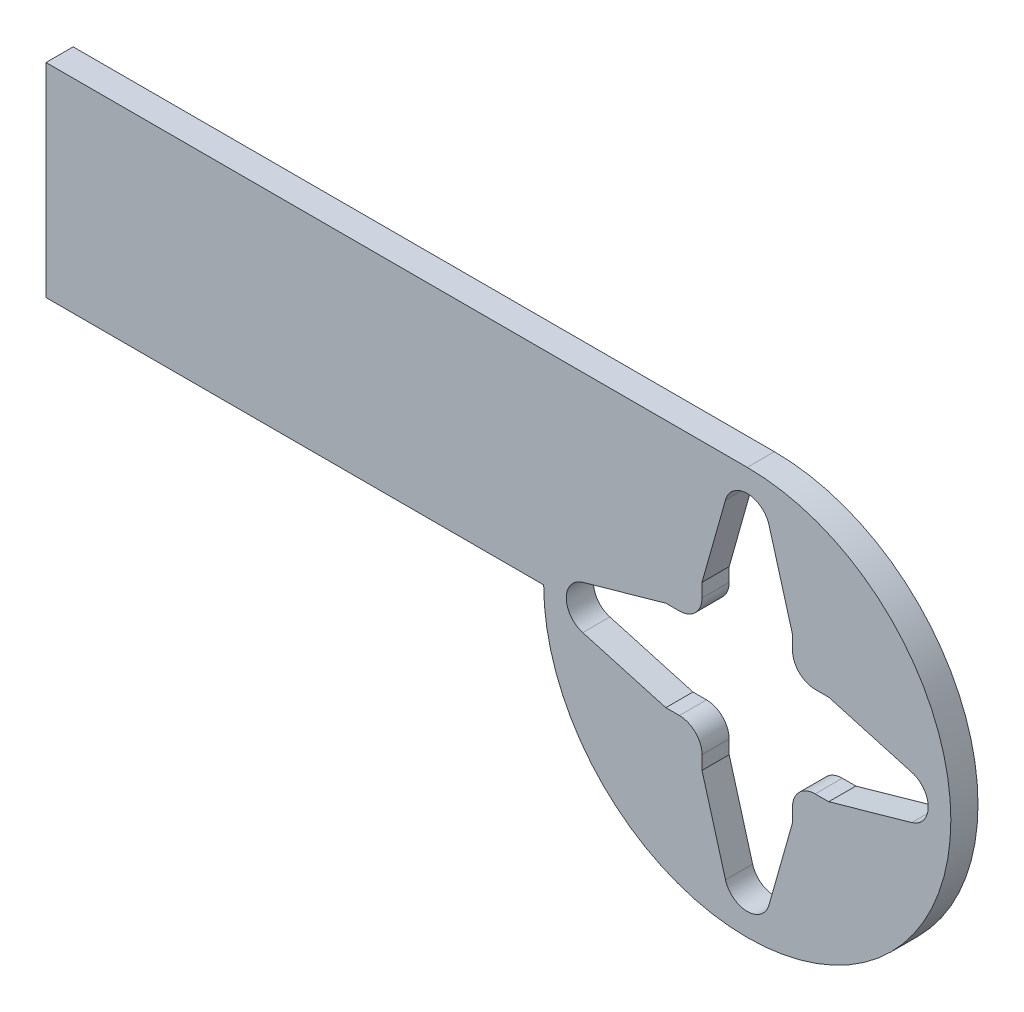
SolidWorks part; units mm, degrees
ref_plane "Front Plane" through (0, 0, 0) normal (0, 0, 1) x (1, 0, 0)
ref_plane "Top Plane" through (0, 0, 0) normal (0, 1, 0) x (1, 0, 0)
ref_plane "Right Plane" through (0, 0, 0) normal (1, 0, 0) x (0, 0, -1)
sketch "Sketch1" plane through (0, 0, 0) normal (0, 0, 1) x (1, 0, 0)
  line L0 (-5, 5) -> (-5, 9)
  line L8 (5, -5) -> (-5, -5)
  line L9 (5, -5) -> (5, 5)
  line L10 (5, 5) -> (-5, 5)
  line L11 (-5, -5) -> (-5, 5)
  line L12 (5, -5) -> (-5, 5) construction
  line L13 (5, 5) -> (-5, -5) construction
  line L14 (-5, 9) -> (-2.4058, 18.1799)
  line L15 (0, -55) -> (0, 55) construction
  line L16 (9, 5) -> (18.1799, 2.4058)
  line L17 (5, 5) -> (5, 9)
  line L18 (55, 0) -> (-55, 0) construction
  line L19 (5, -5) -> (5, -9)
  line L20 (-5, -9) -> (-2.4058, -18.1799)
  line L21 (5, -9) -> (2.4058, -18.1799)
  line L22 (-5, -5) -> (-5, -9)
  line L23 (5, -5) -> (9, -5)
  line L24 (9, -5) -> (18.1799, -2.4058)
  line L25 (-9, -5) -> (-18.1799, -2.4058)
  line L26 (5, 5) -> (9, 5)
  line L27 (-5, -5) -> (-9, -5)
  line L28 (-9, 5) -> (-18.1799, 2.4058)
  line L29 (5, 9) -> (2.4058, 18.1799)
  line L30 (-5, 5) -> (-9, 5)
  line L31 (0, 22.5) -> (-22.5, 0)
  line L32 (-22.5, 0) -> (-22.5, 22.5)
  line L33 (-22.5, 22.5) -> (0, 22.5)
  line L35 (-22.5, 22.5) -> (-77.5, 22.5)
  line L36 (-22.5, 22.5) -> (-22.5, 0)
  line L37 (-22.5, 0) -> (-77.5, 0)
  line L38 (-77.5, 22.5) -> (-77.5, 0)
  circle A0 centre (0, 0) radius 22.5
  circle A1 centre (0, 17.5) radius 2.5
  circle A2 centre (0, -17.5) radius 2.5
  circle A3 centre (17.5, 0) radius 2.5
  circle A4 centre (-17.5, 0) radius 2.5
  circle A5 centre (-7.5, 7.5) radius 2.5
  circle A6 centre (-7.5, -7.5) radius 2.5
  circle A7 centre (7.5, 7.5) radius 2.5
  circle A8 centre (7.5, -7.5) radius 2.5
  arc A9 (-24.8747, 0) -> (-22.3872, -2.25) centre (-24.8747, -2.5) cw
  point P53 (-25.9742, -5)
  point P54 (-22.2598, -3.2792)
  dimension "D1" = 45
  dimension "D3" = 5
  dimension "D5" = 12.5
  dimension "D6" = 5
  dimension "D9" = 5
  dimension "D11" = 2.5
  dimension "D2" = 10
  dimension "D4" = 4
  dimension "D7" = 4
  dimension "D8" = 12.5
  dimension "D10" = 55
extrude "Boss-Extrude1" add sketch "Sketch1" along normal blind 3
